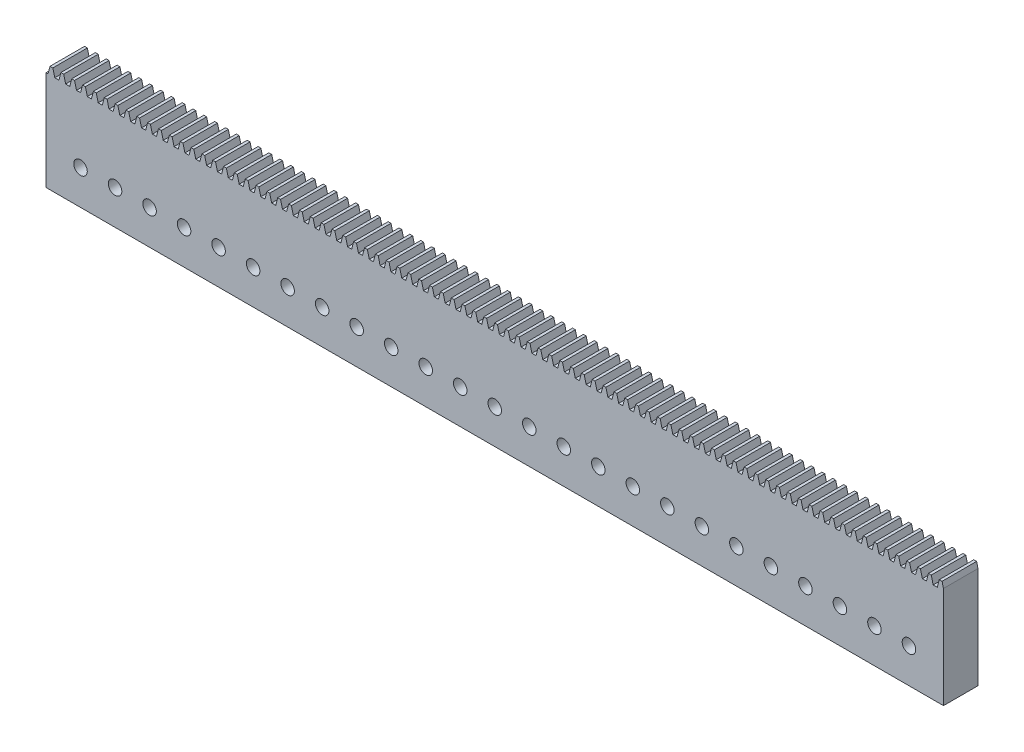
SolidWorks part; units mm, degrees
extrude "Blank" add sketch "BlankSke" against normal blind 12.7
sketch "BlankSke" plane through (0, 0, 0) normal (0, 0, 1) x (1, 0, 0)
  line L1 (0, 0) -> (330.2, 0)
  line L2 (0, 0) -> (0, 39.37)
  line L3 (0, 39.37) -> (330.2, 39.37)
  line L4 (330.2, 0) -> (330.2, 39.37)
  dimension "Length" = 330.2
  dimension "Blank_height" = 39.37
ref_plane "Plane1" through (0, 0, 0) normal (0, 0, 1) x (1, 0, 0)
ref_plane "Plane2" through (0, 0, 0) normal (0, 1, 0) x (1, 0, 0)
ref_plane "Plane3" through (0, 0, 0) normal (1, 0, 0) x (0, 0, -1)
other "Configuration Table"
sketch "HoldingSke" plane through (0, 0, 0) normal (0, 1, 0) x (1, 0, 0)
  line L0 (0, 0) -> (389.1506, -326.5361)
  line L1 (-15, 0) -> (100, 0) construction
  line L2 (0, 0) -> (-2.1039, 2.3779)
  line L3 (0, 0) -> (-11.863, 4.5341)
  line L4 (0, 0) -> (0.9027, 8.5887)
  line L5 (0, 0) -> (-23.7986, -8.8762)
  line L6 (0, 0) -> (-10.5278, -7.1032)
  line L9 (-67.7845, 28.3722) -> (251.8978, 111.0477)
  line L10 (-76.2, 71.12) -> (-38.1, 71.12)
  line L11 (0, 0) -> (-12.7, 0)
  line L12 (-76.2, 101.6) -> (-76.1492, 101.6)
  line L13 (24.9733, 27.94) -> (52.9518, 28.4284)
  line L14 (24.9733, 27.94) -> (25.0241, 27.9398)
  line L15 (24.9733, 27.94) -> (100.4021, 29.52)
  circle A0 centre (0, 0) radius 19.05
  circle A1 centre (0, 0) radius 19.05
  circle A2 centre (0, 0) radius 12.7
  dimension "MPH" = 38.1
  dimension "Diameter" = 38.1
  dimension "Num_teeth" = 84
  dimension "Pitch" = 508
  dimension "Show_teeth" = 400
  dimension "Thickness" = 12.7
  dimension "Ap" = 14.5
  dimension "Pitch_height" = 38.1
  dimension "Width" = 12.7
  dimension "Backlash" = 0.0508
  dimension "Addendum_fac" = 1
  dimension "Dedendum_fac" = 1.2
  dimension "Clearance_fac" = 0.2
  dimension "Dedendum_add" = 0.0508
  dimension "Length" = 330.2
sketch "TooCutSkeIll" plane through (0, 0, 0) normal (0, 0, 1) x (1, 0, 0)
  line L0 (-1.4685, 39.3319) -> (-0.8148, 36.8045)
  line L1 (-0.5197, 36.576) -> (0.5197, 36.576)
  line L2 (0.8148, 36.8045) -> (1.4685, 39.3319)
  line L3 (330.2, 39.37) -> (0, 39.37) construction
  line L4 (0, 0) -> (0, 64.897) construction
  line L5 (-13.208, 38.1) -> (12.954, 38.1) construction
  line L6 (0, 0) -> (330.2, 0) construction
  line L7 (1.1499, 38.1) -> (1.1499, 48.7463) construction
  line L8 (-1.1499, 38.1) -> (-1.1499, 48.7463) construction
  line L9 (1.5176, 39.37) -> (1.5176, 39.3954)
  line L10 (-1.5176, 39.37) -> (-1.5176, 39.3954)
  line L11 (-1.5176, 39.3954) -> (1.5176, 39.3954)
  arc A0 (0.5197, 36.576) -> (0.8148, 36.8045) centre (0.5197, 36.8808) ccw
  arc A1 (-0.8148, 36.8045) -> (-0.5197, 36.576) centre (-0.5197, 36.8808) ccw
  arc A2 (1.5176, 39.37) -> (1.4685, 39.3319) centre (1.5176, 39.3192) ccw
  arc A3 (-1.4685, 39.3319) -> (-1.5176, 39.37) centre (-1.5176, 39.3192) ccw
  dimension "Pitch_height" = 38.1
  dimension "Addendum_plus" = 1.2954
  dimension "Pressure_angle" = 14.5
  dimension "Gap_width" = 2.2997
  dimension "Dedendum" = 1.524
extrude "ToothCutIll" [suppressed] cut sketch "TooCutSkeIll" against normal through all
sketch "TooCutSkeSim" plane through (0, 0, 0) normal (0, 0, 1) x (1, 0, 0)
  line L0 (0.7557, 36.576) -> (-0.7557, 36.576)
  line L1 (1.4849, 39.3954) -> (0.7557, 36.576)
  line L2 (0, 17.4625) -> (0, 53.467) construction
  line L3 (1.4849, 39.3954) -> (-1.4849, 39.3954)
  line L6 (-1.4849, 39.3954) -> (-0.7557, 36.576)
  line L9 (-1.1499, 38.1) -> (1.1499, 38.1) construction
  line L10 (0, 0) -> (330.2, 0) construction
  line L11 (1.1499, 38.1) -> (1.1499, 53.467) construction
  line L12 (-1.1499, 38.1) -> (-1.1499, 53.467) construction
  dimension "Pitch_height" = 38.1
  dimension "Addendum_plus" = 1.2954
  dimension "Pressure_angle" = 14.5
  dimension "Gap_width" = 2.2997
  dimension "Dedendum" = 1.524
extrude "ToothCutSim" cut sketch "TooCutSkeSim" against normal through all
pattern_linear "TeethCuts" count 83 spacing 3.9898 along (1, 0, 0) of "ToothCutIll", "ToothCutSim"
sketch "Sketch1" plane through (0, 0, 0) normal (0, 0, 1) x (1, 0, 0)
  line L0 (0, 0) -> (330.2, 0) construction
  line L1 (0, 36.576) -> (0, 0) construction
  point P0 (12.7, 12.7)
  point P1 (25.4, 12.7)
  point P2 (38.1, 12.7)
  point P3 (0, 0)
  point P4 (50.8, 12.7)
  point P5 (63.5, 12.7)
  point P6 (76.2, 12.7)
  point P7 (88.9, 12.7)
  point P8 (101.6, 12.7)
  point P9 (114.3, 12.7)
  point P10 (127, 12.7)
  point P11 (139.7, 12.7)
  point P12 (152.4, 12.7)
  point P13 (165.1, 12.7)
  point P14 (177.8, 12.7)
  point P15 (190.5, 12.7)
  point P16 (203.2, 12.7)
  point P17 (215.9, 12.7)
  point P18 (228.6, 12.7)
  point P19 (241.3, 12.7)
  point P20 (254, 12.7)
  point P21 (266.7, 12.7)
  point P22 (279.4, 12.7)
  point P23 (292.1, 12.7)
  point P24 (304.8, 12.7)
  point P25 (317.5, 12.7)
  point P30 (0, 0)
  point P31 (30.5868, 12.7)
  dimension "D2" = 12.7
  dimension "D3" = 12.7
  dimension "D4" = 12.7
  dimension "D1" = 25
hole_wizard "#9 (0.196) Diameter Hole1" positions "Sketch1" profile "Sketch2" hole size "#9" standard "ANSI Inch" end condition through all
sketch "Sketch2" plane through (12.7, 12.7, 0) normal (1, 0, 0) x (0, -1, 0)
  line L0 (0, 0) -> (0, 12.7)
  line L1 (0, 12.7) -> (2.4892, 12.7)
  line L2 (2.4892, 12.7) -> (2.4892, 0)
  line L5 (2.4892, 0) -> (0, 0)
  line L11 (0, -6.35) -> (0, 107.95) construction
  dimension "Thru Hole Dia." = 4.9784
  dimension "Thru Hole Depth" = 12.7
equation "' \"Pitch@HoldingSke\" = 4"
equation "' \"Num_teeth@HoldingSke\" = 12"
equation "' \"Ap@HoldingSke\" =  20"
equation "' \"Ap@HoldingSke\" = 20"
equation "' \"Width@HoldingSke\" = 0.25"
equation "' \"Show_teeth@HoldingSke\" = 500"
equation "' \"Backlash@HoldingSke\" = 0.009"
equation "' \"Addendum_fac@HoldingSke\" = 1.0"
equation "' \"Dedendum_fac@HoldingSke\" = 1.25"
equation "' \"Dedendum_add@HoldingSke\" = 0.00005"
equation "' \"Clearance_fac@HoldingSke\" = 0.25"
equation "' \"Pitch_height@HoldingSke\" = 1"
equation "' \"Length@HoldingSke\" = 4.71"
equation "\"MPH@HoldingSke\" = \"Dedendum_fac@HoldingSke\" / \"Pitch@HoldingSke\" + 2 * \"Dedendum_add@HoldingSke\" + 0.002"
equation "\"MPH@HoldingSke\" = ((sgn( \"MPH@HoldingSke\" - \"Pitch_height@HoldingSke\")+1)*( \"MPH@HoldingSke\" - \"Pitch_height@HoldingSke\"))/2 + \"Pitch_height@HoldingSke\""
equation "\"Blank_height@BlankSke\" = \"Pitch_height@HoldingSke\" + \"Addendum_fac@HoldingSke\"  / \"Pitch@HoldingSke\" "
equation "\"Length@BlankSke\" =  \"Length@HoldingSke\""
equation "\"Face_width@Blank\" = \"Width@HoldingSke\""
equation "\"Pressure_angle@TooCutSkeIll\" = \"Ap@HoldingSke\""
equation "\"Addendum_plus@TooCutSkeIll\" =  \"Addendum_fac@HoldingSke\"  / \"Pitch@HoldingSke\" + 0.001"
equation "\"Dedendum@TooCutSkeIll\" = \"Dedendum_fac@HoldingSke\"  / \"Pitch@HoldingSke\""
equation "\"Pitch_height@TooCutSkeIll\" =  \"MPH@HoldingSke\""
equation "\"Gap_width@TooCutSkeIll\" = 3.14159265 / 2 / \"Pitch@HoldingSke\" + 6 * \"Backlash@HoldingSke\""
equation "\"Pressure_angle@TooCutSkeSim\" = \"Ap@HoldingSke\""
equation "\"Addendum_plus@TooCutSkeSim\" =  \"Addendum_fac@HoldingSke\"  / \"Pitch@HoldingSke\" + 0.001"
equation "\"Dedendum@TooCutSkeSim\" = \"Dedendum_fac@HoldingSke\"  / \"Pitch@HoldingSke\""
equation "\"Pitch_height@TooCutSkeSim\" =  \"MPH@HoldingSke\""
equation "\"Gap_width@TooCutSkeSim\" = 3.14159265 / 2 / \"Pitch@HoldingSke\" + 6 * \"Backlash@HoldingSke\""
equation "\"Root_fillet@TooCutSkeIll\" = \"Clearance_fac@HoldingSke\" / \"Pitch@HoldingSke\" + \"Dedendum_add@HoldingSke\""
equation "\"Break_rad@TooCutSkeIll\" = 0.02 / \"Pitch@HoldingSke\" * 2"
equation "\"Linear_pitch@TeethCuts\" = 3.14159265 / \"Pitch@HoldingSke\""
equation "\"Num_teeth@HoldingSke\" = int( ( \"Length@HoldingSke\" + 0 ) / (3.14159265 / \"Pitch@HoldingSke\")) + 0.9999  + 1"
equation " \"Num_teeth@TeethCuts\" = int( \"Show_teeth@HoldingSke\" ) + 1"
equation " \"Num_teeth@TeethCuts\" = ((sgn( \"Num_teeth@TeethCuts\" - \"Num_teeth@HoldingSke\" )-1)*( \"Num_teeth@TeethCuts\" - \"Num_teeth@HoldingSke\" ))/-2+ \"Num_teeth@HoldingSke\""
equation " \"Num_teeth@TeethCuts\" = ((sgn( \"Num_teeth@TeethCuts\" - 2.0)+1)*( \"Num_teeth@TeethCuts\" - 2.0))/2 +2.0"
